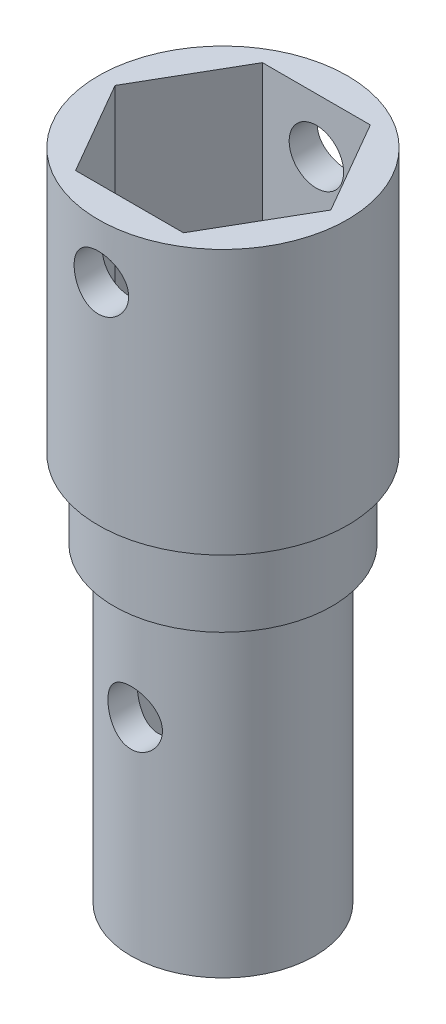
SolidWorks part; units mm, degrees
ref_plane "Front Plane" through (0, 0, 0) normal (0, 0, 1) x (1, 0, 0)
ref_plane "Top Plane" through (0, 0, 0) normal (0, 1, 0) x (1, 0, 0)
ref_plane "Right Plane" through (0, 0, 0) normal (1, 0, 0) x (0, 0, -1)
sketch "Sketch1" plane through (0, 0, 0) normal (0, -1, 0) x (1, 0, 0)
  line L1 (6.9282, 0) -> (3.4641, 6)
  line L2 (3.4641, 6) -> (-3.4641, 6)
  line L3 (-3.4641, 6) -> (-6.9282, 0)
  line L4 (-6.9282, 0) -> (-3.4641, -6)
  line L5 (-3.4641, -6) -> (3.4641, -6)
  line L6 (3.4641, -6) -> (6.9282, 0)
  circle A0 centre (0, 0) radius 8
  circle A1 centre (0, 0) radius 6 construction
  dimension "D1" = 16
  dimension "D2" = 6.9282
  dimension "D3" = 6
extrude "Boss-Extrude1" add sketch "Sketch1" against normal blind 17
sketch "Sketch2" plane through (0, 0, -6) normal (0, 0, 1) x (1, 0, 0)
  line L0 (0, 0) -> (0, 11.75) construction
  arc A0 (0, 15.25) -> (-1.75, 13.5) centre (0, 13.5) ccw construction
  arc A1 (1.75, 13.5) -> (0, 15.25) centre (0, 13.5) ccw construction
  arc A2 (1.75, 13.5) -> (0, 15.25) centre (0, 13.5) ccw construction
  arc A3 (0, 15.25) -> (-1.75, 13.5) centre (0, 13.5) ccw construction
  arc A4 (-1.75, 13.5) -> (0, 11.75) centre (0, 13.5) ccw construction
  arc A5 (-1.75, 13.5) -> (0, 11.75) centre (0, 13.5) ccw construction
  arc A6 (0, 11.75) -> (1.75, 13.5) centre (0, 13.5) ccw construction
  arc A7 (0, 11.75) -> (1.75, 13.5) centre (0, 13.5) ccw construction
  arc A8 (0, 15.25) -> (-1.75, 13.5) centre (0, 13.5) ccw
  arc A9 (1.75, 13.5) -> (0, 15.25) centre (0, 13.5) ccw
  arc A10 (1.75, 13.5) -> (0, 15.25) centre (0, 13.5) ccw
  arc A11 (0, 15.25) -> (-1.75, 13.5) centre (0, 13.5) ccw
  arc A12 (-1.75, 13.5) -> (0, 11.75) centre (0, 13.5) ccw
  arc A13 (-1.75, 13.5) -> (0, 11.75) centre (0, 13.5) ccw
  arc A14 (0, 11.75) -> (1.75, 13.5) centre (0, 13.5) ccw
  arc A15 (0, 11.75) -> (1.75, 13.5) centre (0, 13.5) ccw
extrude "Cut-Extrude2" cut sketch "Sketch2" against normal through all and the other way through all contours A12 A14 A9 A8
sketch "Sketch3" plane through (0, 0, 0) normal (0, -1, 0) x (1, 0, 0)
  circle A0 centre (0, 0) radius 4.15
  circle A1 centre (0, 0) radius 5.9002
  dimension "D1" = 8.3
  dimension "D2" = 11.8004
extrude "Boss-Extrude2" add sketch "Sketch3" along normal blind 25
sketch "Sketch4" plane through (0, 0, 0) normal (0, 0, 1) x (1, 0, 0)
  line L0 (0, -11.75) -> (0, 11.75) construction
  circle A0 centre (0, 13.5) radius 1.75 construction
  circle A1 centre (0, -11.75) radius 1.75
  point P4 (0, 0)
  dimension "D1" = 3.5
extrude "Cut-Extrude3" cut sketch "Sketch4" against normal through all and the other way through all
sketch "Sketch5" plane through (0, 0, 0) normal (0, -1, 0) x (1, 0, 0)
  circle A0 centre (0, 0) radius 5.9002
  circle A1 centre (0, 0) radius 7
  dimension "D1" = 14
  dimension "D2" = 11.8004
extrude "Boss-Extrude3" add sketch "Sketch5" along normal blind 5
